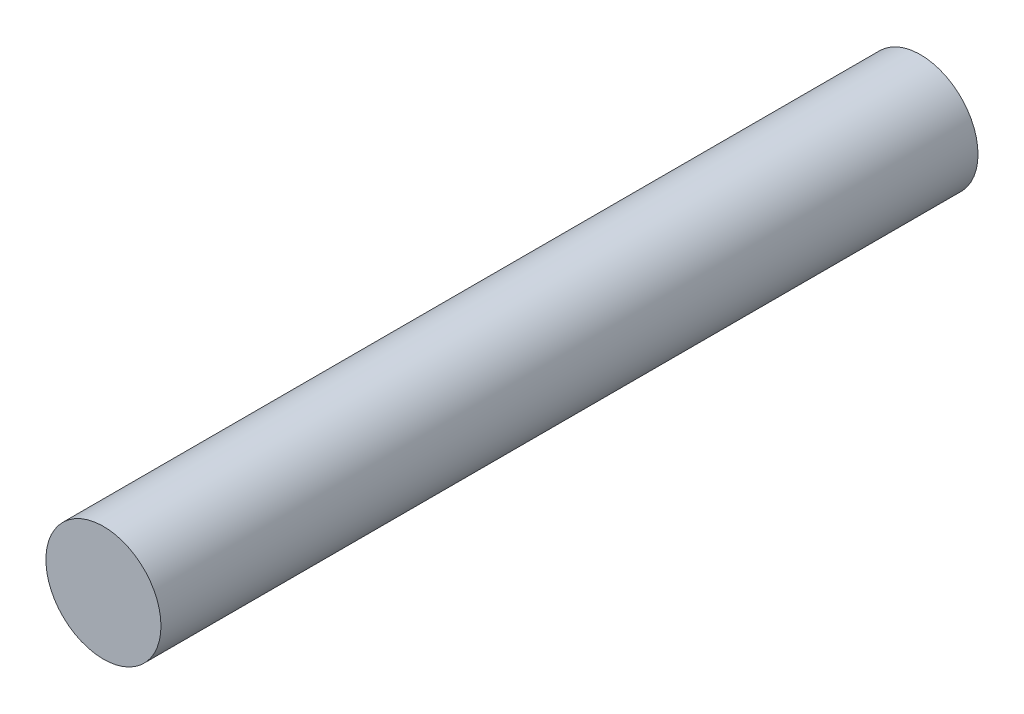
SolidWorks part; units mm, degrees
material "AISI 304"
ref_plane "Front Plane" through (0, 0, 0) normal (0, 0, 1) x (1, 0, 0)
ref_plane "Top Plane" through (0, 0, 0) normal (0, 1, 0) x (1, 0, 0)
ref_plane "Right Plane" through (0, 0, 0) normal (1, 0, 0) x (0, 0, -1)
sketch "Sketch1" plane through (0, 0, 0) normal (0, 0, 1) x (1, 0, 0)
  circle A0 centre (0, 0) radius 4
  dimension "D1" = 8
extrude "Boss-Extrude1" add sketch "Sketch1" along normal blind 56.8
